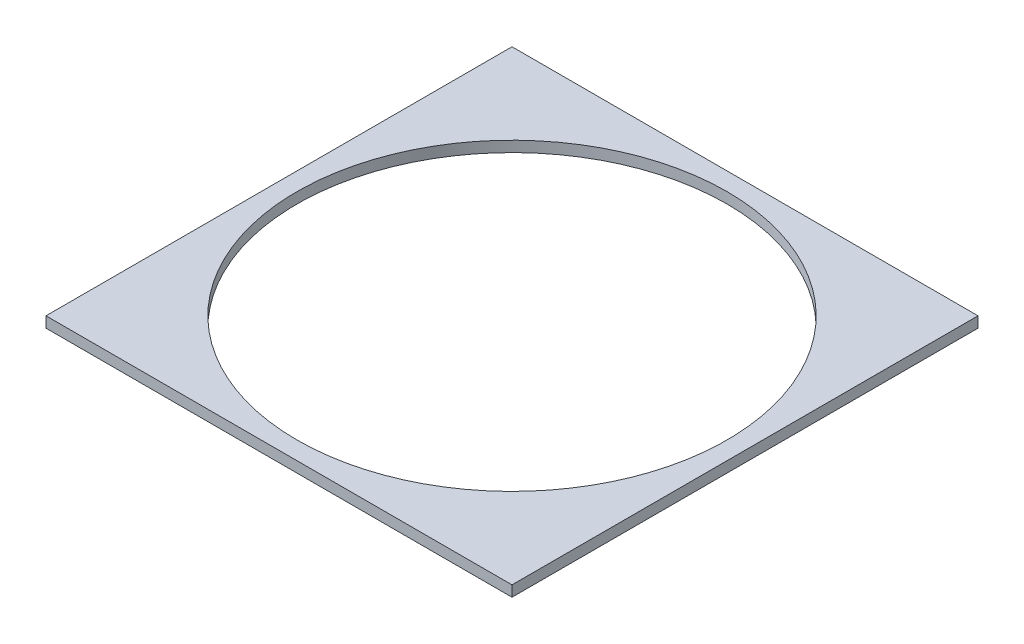
SolidWorks part; units mm, degrees
ref_plane "Front Plane" through (0, 0, 0) normal (0, 0, 1) x (1, 0, 0)
ref_plane "Top Plane" through (0, 0, 0) normal (0, 1, 0) x (1, 0, 0)
ref_plane "Right Plane" through (0, 0, 0) normal (1, 0, 0) x (0, 0, -1)
sketch "Sketch1" plane through (0, 0, 0) normal (0, 1, 0) x (1, 0, 0)
  line L1 (-165.1, 165.1) -> (165.1, 165.1)
  line L2 (-165.1, 165.1) -> (-165.1, -165.1)
  line L3 (-165.1, -165.1) -> (165.1, -165.1)
  line L4 (165.1, 165.1) -> (165.1, -165.1)
  line L5 (-165.1, 165.1) -> (165.1, -165.1) construction
  line L6 (-165.1, -165.1) -> (165.1, 165.1) construction
  circle A0 centre (0, 0) radius 152.4
  point P0 (0, 0)
  dimension "D3" = 304.8
  dimension "D1" = 330.2
  dimension "D2" = 330.2
extrude "Boss-Extrude1" add sketch "Sketch1" along normal blind 7.62
